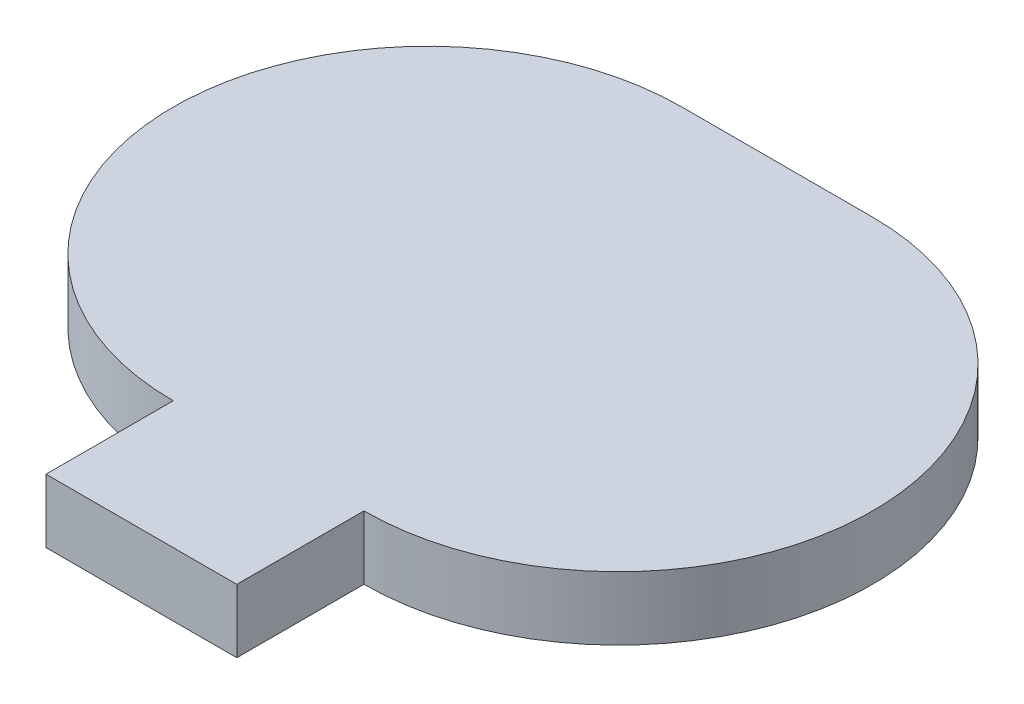
SolidWorks part; units mm, degrees
ref_plane "Front Plane" through (0, 0, 0) normal (0, 0, 1) x (1, 0, 0)
ref_plane "Top Plane" through (0, 0, 0) normal (0, 1, 0) x (1, 0, 0)
ref_plane "Right Plane" through (0, 0, 0) normal (1, 0, 0) x (0, 0, -1)
sketch "Sketch1" plane through (0, 0, 0) normal (0, 1, 0) x (1, 0, 0)
  line L0 (-3, 0) -> (3, 0) construction
  line L1 (3, 0) -> (3, 20) construction
  line L2 (3, 20) -> (-3, 20) construction
  line L3 (-3, 20) -> (-3, 0) construction
  line L5 (-3, 4) -> (3, 4) construction
  line L6 (-3, 4) -> (-3, 0)
  line L7 (-3, 0) -> (3, 0)
  line L8 (3, 0) -> (3, 4)
  line L9 (-3, 20) -> (3, 20)
  arc A0 (-3, 20) -> (-3, 4) centre (-3, 12) ccw
  arc A1 (3, 20) -> (3, 4) centre (3, 12) cw
  dimension "D1" = 20
  dimension "D2" = 6
  dimension "D3" = 3
  dimension "D4" = 4
extrude "Boss-Extrude1" add sketch "Sketch1" along normal blind 2
